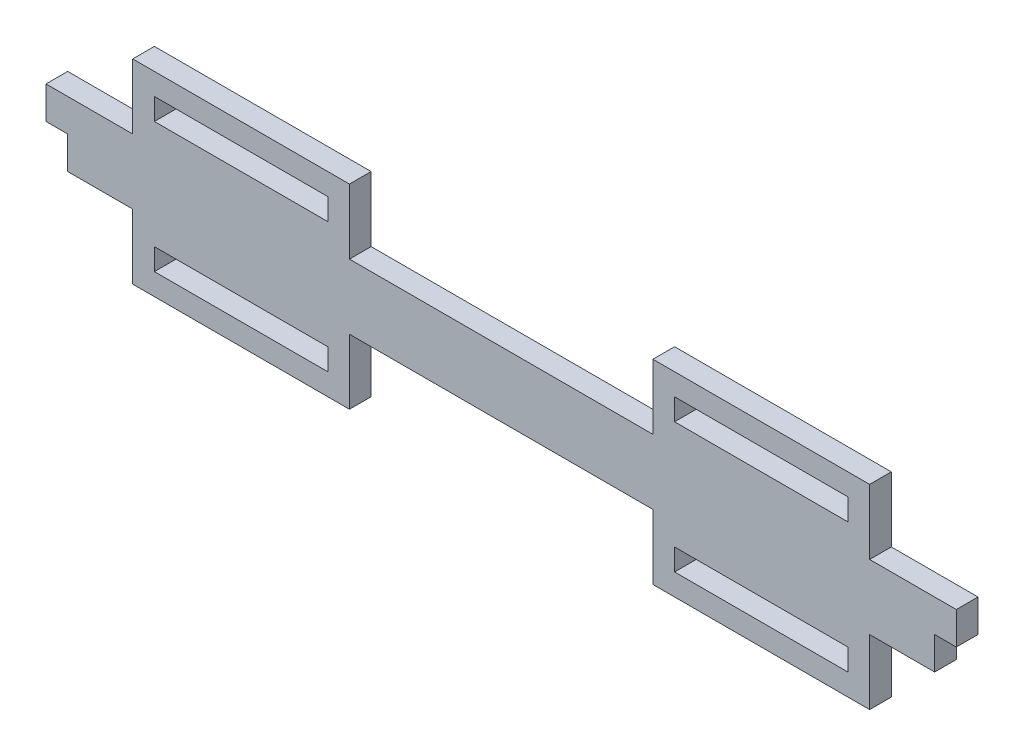
SolidWorks part; units mm, degrees
ref_plane "Front Plane" through (0, 0, 0) normal (0, 0, 1) x (1, 0, 0)
ref_plane "Top Plane" through (0, 0, 0) normal (0, 1, 0) x (1, 0, 0)
ref_plane "Right Plane" through (0, 0, 0) normal (1, 0, 0) x (0, 0, -1)
sketch "Sketch1" plane through (0, 0, 0) normal (0, 0, 1) x (1, 0, 0)
  line L1 (0, 0) -> (-210, 0)
  line L2 (0, 0) -> (0, 15)
  line L3 (0, 15) -> (-210, 15)
  line L4 (-210, 0) -> (-210, 15)
  dimension "D1" = 15
  dimension "D2" = 210
extrude "Boss-Extrude1" add sketch "Sketch1" along normal blind 5
sketch "Sketch2" plane through (0, 0, 0) normal (0, 0, -1) x (-1, 0, 0)
  line L0 (210, 0) -> (0, 0) construction
  line L1 (20, 0) -> (70, 0)
  line L2 (20, 0) -> (20, -5)
  line L3 (20, -5) -> (70, -5)
  line L4 (70, 0) -> (70, -5)
  line L5 (0, 0) -> (0, 15) construction
  line L6 (105, 15) -> (105, -11.8988) construction
  line L7 (0, 15) -> (210, 15) construction
  line L8 (140, 0) -> (140, -5)
  line L9 (190, -5) -> (140, -5)
  line L10 (190, 0) -> (190, -5)
  line L11 (190, 0) -> (140, 0)
  line L12 (0, 7.5) -> (35.9218, 7.5) construction
  line L13 (190, 15) -> (140, 15)
  line L14 (190, 15) -> (190, 20)
  line L15 (190, 20) -> (140, 20)
  line L16 (140, 15) -> (140, 20)
  line L17 (20, 20) -> (70, 20)
  line L18 (70, 15) -> (70, 20)
  line L19 (20, 15) -> (70, 15)
  line L20 (20, 15) -> (20, 20)
  dimension "D1" = 5
  dimension "D2" = 20
  dimension "D3" = 50
extrude "Boss-Extrude2" add sketch "Sketch2" against normal blind 5
sketch "Sketch3" plane through (0, 0, 0) normal (0, 0, -1) x (-1, 0, 0)
  line L0 (0, 0) -> (0, 15) construction
  line L1 (0, 7.5) -> (5, 7.5)
  line L2 (0, 7.5) -> (0, 0)
  line L3 (0, 0) -> (5, 0)
  line L4 (5, 7.5) -> (5, 0)
  line L5 (20, 0) -> (0, 0) construction
  line L6 (105, 15) -> (105, 8.5536) construction
  line L7 (70, 15) -> (140, 15) construction
  line L8 (205, 7.5) -> (205, 0)
  line L9 (210, 0) -> (205, 0)
  line L10 (210, 7.5) -> (210, 0)
  line L11 (210, 7.5) -> (205, 7.5)
  dimension "D1" = 5
  dimension "D2" = 7.5
extrude "Cut-Extrude1" cut sketch "Sketch3" against normal blind 5
sketch "Sketch4" plane through (0, 0, 0) normal (0, 0, -1) x (-1, 0, 0)
  line L0 (105, 15) -> (105, -21.2598) construction
  line L1 (140, 20) -> (190, 20)
  line L2 (140, 20) -> (140, 30)
  line L3 (140, 30) -> (190, 30)
  line L4 (190, 20) -> (190, 30)
  line L5 (145, 20) -> (185, 20)
  line L6 (145, 20) -> (145, 25)
  line L7 (145, 25) -> (185, 25)
  line L8 (185, 20) -> (185, 25)
  line L9 (70, 15) -> (140, 15) construction
  line L10 (25, 20) -> (25, 25)
  line L11 (65, 25) -> (25, 25)
  line L12 (65, 20) -> (65, 25)
  line L13 (65, 20) -> (25, 20)
  line L14 (20, 20) -> (20, 30)
  line L15 (70, 30) -> (20, 30)
  line L16 (70, 20) -> (70, 30)
  line L17 (70, 20) -> (20, 20)
  line L18 (5, 7.5) -> (27.0833, 7.5) construction
  line L19 (70, -5) -> (20, -5)
  line L20 (70, -5) -> (70, -15)
  line L21 (70, -15) -> (20, -15)
  line L22 (20, -5) -> (20, -15)
  line L23 (65, -5) -> (25, -5)
  line L24 (65, -5) -> (65, -10)
  line L25 (65, -10) -> (25, -10)
  line L26 (25, -5) -> (25, -10)
  line L27 (185, -5) -> (185, -10)
  line L28 (145, -10) -> (185, -10)
  line L29 (145, -5) -> (145, -10)
  line L30 (145, -5) -> (185, -5)
  line L31 (190, -5) -> (190, -15)
  line L32 (140, -15) -> (190, -15)
  line L33 (140, -5) -> (140, -15)
  line L34 (140, -5) -> (190, -5)
  line M20 (20, -5) -> (70, -5)
  line M24 (140, -5) -> (190, -5)
  line M32 (190, 20) -> (140, 20)
  line M36 (70, 20) -> (20, 20)
  dimension "D1" = 10
  dimension "D2" = 50
  dimension "D3" = 40
  dimension "D4" = 5
  dimension "D5" = 5
extrude "Boss-Extrude3" add sketch "Sketch4" against normal blind 5 contours L8 L4 L3 L2 L6 L7 M32 | L16 L15 L14 L10 L11 L12 M36 | L26 L22 L21 L20 L24 L25 M20 | L33 L32 L31 L27 L28 L29 M24
